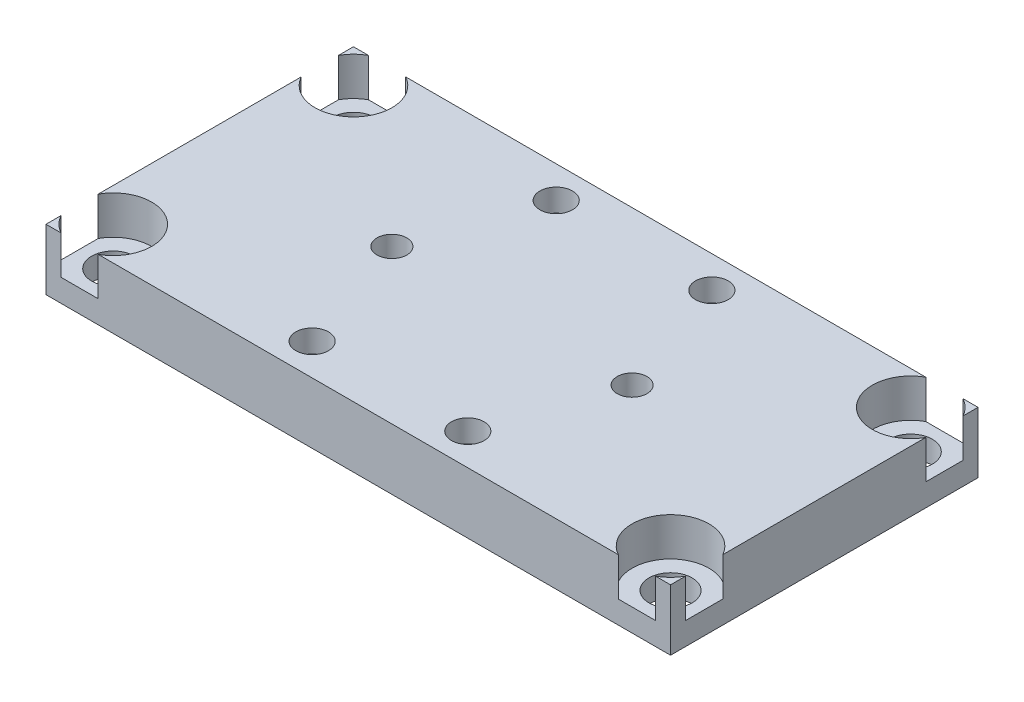
SolidWorks part; units mm, degrees
ref_plane "Front Plane" through (0, 0, 0) normal (0, 0, 1) x (1, 0, 0)
ref_plane "Top Plane" through (0, 0, 0) normal (0, 1, 0) x (1, 0, 0)
ref_plane "Right Plane" through (0, 0, 0) normal (1, 0, 0) x (0, 0, -1)
sketch "Sketch1" plane through (0, 0, 0) normal (0, 1, 0) x (1, 0, 0)
  line L1 (-32.5, -16) -> (32.5, -16)
  line L2 (-32.5, -16) -> (-32.5, 16)
  line L3 (-32.5, 16) -> (32.5, 16)
  line L4 (32.5, -16) -> (32.5, 16)
  line L5 (-32.5, -16) -> (32.5, 16) construction
  line L6 (-32.5, 16) -> (32.5, -16) construction
  point P0 (0, 0)
  dimension "D1" = 65
  dimension "D2" = 32
extrude "Extrude1" add sketch "Sketch1" along normal blind 6.35
sketch "Sketch3" plane through (0, 6.35, 0) normal (0, 1, 0) x (-1, 0, 0)
  line L0 (0, -24.9352) -> (0, 26.0817) construction
  line L1 (37.4888, 0) -> (-41.0428, 0) construction
hole_wizard "CBORE for M4 SHCS1" positions "3DSketch3" profile "Sketch5" counterbore size "M4" standard "Ansi Metric" end condition through all
sketch3d "3DSketch3"
  line L0 (-37.4888, 6.35, 0) -> (41.0428, 6.35, 0) construction
  line L1 (0, 6.35, -24.9352) -> (0, 6.35, 26.0817) construction
  point P0 (-29, 6.35, -12.5)
  dimension "D1" = 12.5
  dimension "D2" = 29
sketch "Sketch5" plane through (-29, 6.35, -12.5) normal (1, 0, 0) x (0, 0, 1)
  line L0 (0, 0) -> (0, 6.35)
  line L1 (0, 6.35) -> (2.25, 6.35)
  line L3 (2.25, 6.35) -> (2.25, 4)
  line L4 (2.25, 4) -> (4, 4)
  line L5 (4, 4) -> (4, 0)
  line L7 (4, 0) -> (0, 0)
  line L11 (0, -6.35) -> (0, 107.95) construction
  dimension "Thru Hole Dia." = 4.5
  dimension "Thru Hole Depth" = 6.35
  dimension "C'Bore Dia." = 8
  dimension "C'Bore Depth" = 4
pattern_linear "LPattern2" count 2 spacing 58 along (1, 0, 0) count 2 spacing 25 along (0, 0, 1) of "CBORE for M4 SHCS1"
sketch "Sketch6" plane through (0, 0, 0) normal (0, -1, 0) x (1, 0, 0)
  line L0 (38.0396, 0) -> (-36.8904, 0) construction
  line L1 (0, -22.4675) -> (0, 19.9392) construction
hole_wizard "CBORE for M3 SHCS1" positions "3DSketch4" profile "Sketch7" counterbore size "M3" standard "Ansi Metric" end condition through all
sketch3d "3DSketch4"
  line L0 (0, 0, -22.4675) -> (0, 0, 19.9392) construction
  line L1 (38.0396, 0, 0) -> (-36.8904, 0, 0) construction
  point P0 (-8.1, 0, 12.7)
  dimension "D1" = 8.1
  dimension "D2" = 12.7
sketch "Sketch7" plane through (-8.1, 0, 12.7) normal (1, 0, 0) x (0, 0, -1)
  line L0 (0, 0) -> (0, 6.35)
  line L1 (0, 6.35) -> (1.7, 6.35)
  line L3 (1.7, 6.35) -> (1.7, 4)
  line L4 (1.7, 4) -> (3.25, 4)
  line L5 (3.25, 4) -> (3.25, 0)
  line L7 (3.25, 0) -> (0, 0)
  line L11 (0, -6.35) -> (0, 107.95) construction
  dimension "Thru Hole Dia." = 3.4
  dimension "Thru Hole Depth" = 6.35
  dimension "C'Bore Dia." = 6.5
  dimension "C'Bore Depth" = 4
pattern_linear "LPattern3" count 2 spacing 16.2 along (1, 0, 0) count 2 spacing 25.4 along (0, 0, -1) of "CBORE for M3 SHCS1"
hole_wizard "Ø3.1 (3.1) Diameter Hole1" positions "3DSketch5" profile "Sketch8" hole size "Ø3.1" standard "Ansi Metric"
sketch3d "3DSketch5"
  line L0 (-37.4888, 6.35, 0) -> (41.0428, 6.35, 0) construction
  line L1 (0, 6.35, -24.9352) -> (0, 6.35, 26.0817) construction
  point P0 (-12.5, 6.35, 0)
  dimension "D1" = 12.5
sketch "Sketch8" plane through (-12.5, 6.35, 0) normal (1, 0, 0) x (0, 0, 1)
  line L0 (0, 0) -> (0, 5.9313)
  line L1 (0, 5.9313) -> (1.55, 5)
  line L2 (1.55, 5) -> (1.55, 0)
  line L5 (1.55, 0) -> (0, 0)
  line L10 (0, 5.9313) -> (-1.55, 5) construction
  line L11 (0, -6.35) -> (0, 107.95) construction
  dimension "Hole Dia." = 3.1
  dimension "Hole Depth" = 5
  dimension "Drill Angle" = 118
pattern_linear "LPattern4" count 2 spacing 25 along (1, 0, 0) of "Ø3.1 (3.1) Diameter Hole1"
